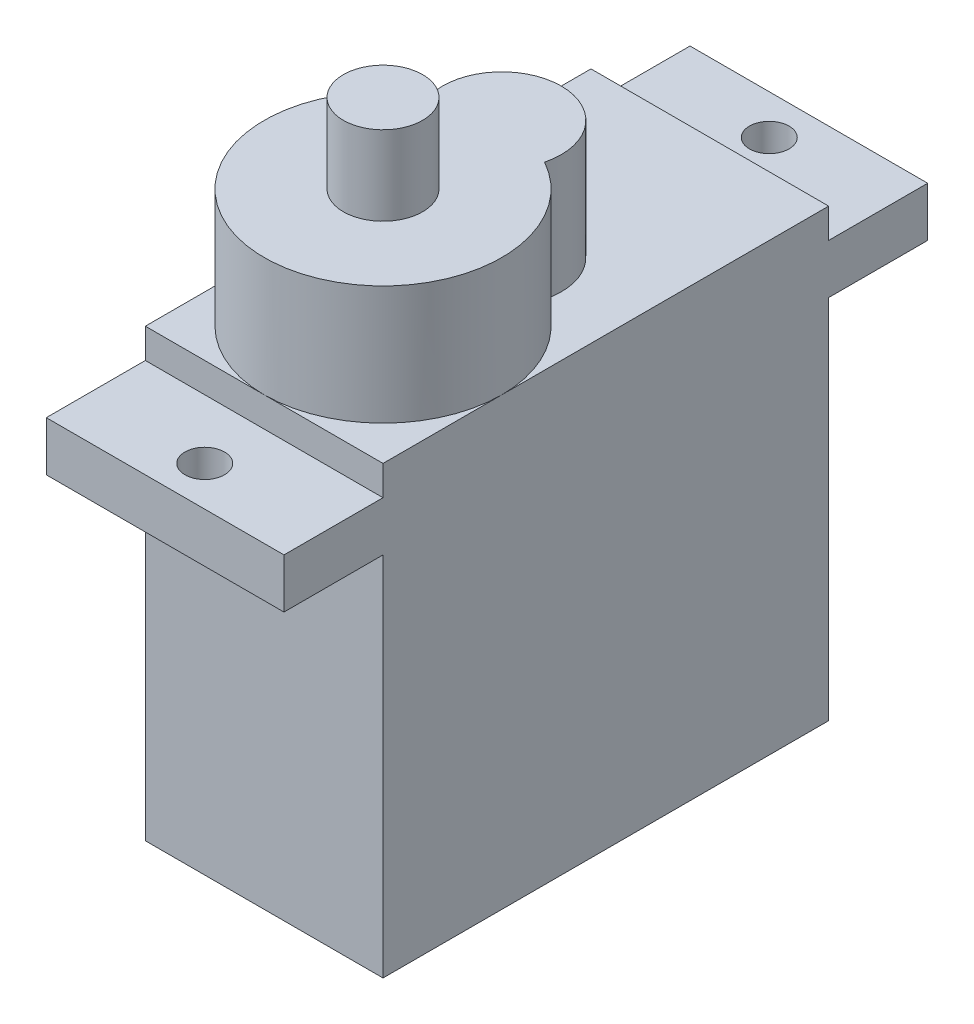
SolidWorks part; units mm, degrees
material "Servo"
ref_plane "前基準面" through (0, 0, 0) normal (0, 0, 1) x (1, 0, 0)
ref_plane "上基準面" through (0, 0, 0) normal (0, 1, 0) x (1, 0, 0)
ref_plane "右基準面" through (0, 0, 0) normal (1, 0, 0) x (0, 0, -1)
sketch "草圖1" plane through (0, 0, 0) normal (1, 0, 0) x (0, 0, -1)
  line L0 (11.25, 11.75) -> (16.25, 11.75)
  line L2 (-11.25, 9.25) -> (-11.25, -9.25)
  line L3 (-11.25, -9.25) -> (11.25, -9.25)
  line L4 (11.25, 9.25) -> (11.25, -9.25)
  line L5 (-11.25, 9.25) -> (11.25, -9.25) construction
  line L6 (-11.25, -9.25) -> (11.25, 9.25) construction
  line L7 (-16.25, 11.75) -> (-11.25, 11.75)
  line L8 (-16.25, 11.75) -> (-16.25, 9.25)
  line L9 (-16.25, 9.25) -> (-11.25, 9.25)
  line L10 (16.25, 11.75) -> (16.25, 9.25)
  line L11 (-16.25, 11.75) -> (16.25, 9.25) construction
  line L12 (-16.25, 9.25) -> (16.25, 11.75) construction
  line L13 (-11.25, 13.25) -> (11.25, 13.25)
  line L14 (-11.25, 13.25) -> (-11.25, 11.75)
  line L16 (11.25, 13.25) -> (11.25, 11.75)
  line L17 (-11.25, 13.25) -> (11.25, 11.75) construction
  line L18 (-11.25, 11.75) -> (11.25, 13.25) construction
  line L19 (11.25, 9.25) -> (16.25, 9.25)
  line L20 (0, 12.5) -> (0, 0) construction
  point P0 (0, 0)
  point P6 (0, 10.5)
  point P11 (0, 12.5)
  dimension "D1" = 22.5
  dimension "D2" = 21
  dimension "D3" = 22.5
  dimension "D4" = 2.5
  dimension "D5" = 32.5
extrude "填料-伸長1" add sketch "草圖1" along normal blind 12
sketch "草圖2" plane through (0, 13.25, 0) normal (0, 1, 0) x (1, 0, 0)
  line L1 (12, -11.25) -> (0, -11.25) construction
  line L3 (0, 11.25) -> (0, -11.25) construction
  line L4 (12, 11.25) -> (12, -11.25) construction
  line L5 (6, -11.25) -> (6, 11.25) construction
  line L6 (12, 11.25) -> (0, 11.25) construction
  arc A0 (3.0953, 0) -> (8.9047, 0) centre (6, -5.25) ccw
  arc A1 (8.9047, 0) -> (3.0953, 0) centre (6, 0.75) ccw
  dimension "D1" = 6
  dimension "D2" = 6
extrude "填料-伸長2" add sketch "草圖2" along normal blind 6
sketch "草圖3" plane through (0, 19.25, 0) normal (0, 1, 0) x (1, 0, 0)
  circle A0 centre (6, -5.25) radius 2
  dimension "D1" = 4
extrude "填料-伸長3" add sketch "草圖3" along normal blind 4
sketch "草圖4" plane through (0, 11.75, 0) normal (0, 1, 0) x (1, 0, 0)
  line L0 (6, -16.25) -> (6, 16.25) construction
  line L1 (12, -16.25) -> (0, -16.25) construction
  line L2 (12, 16.25) -> (0, 16.25) construction
  circle A0 centre (6, -14.25) radius 1
  circle A1 centre (6, 14.25) radius 1
  dimension "D3" = 2
  dimension "D1" = 2
  dimension "D2" = 2
  dimension "D4" = 28.5
extrude "除料-伸長1" cut sketch "草圖4" against normal through all
